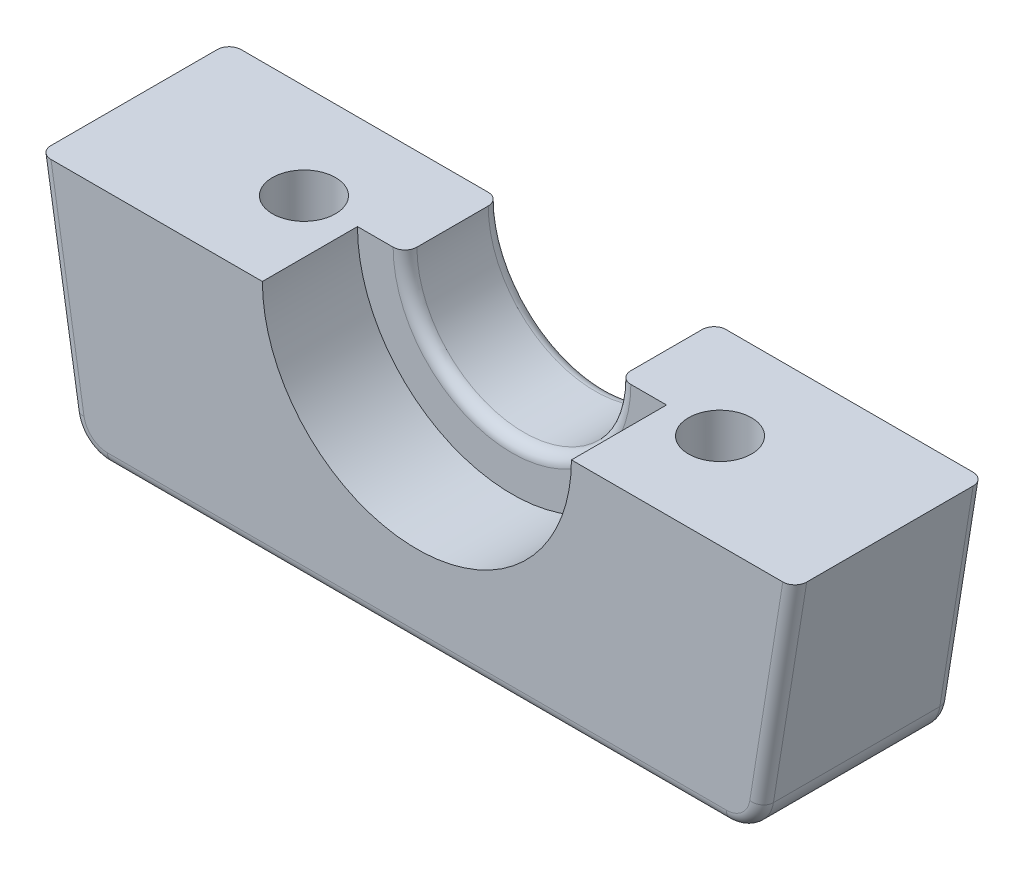
SolidWorks part; units mm, degrees
ref_plane "Płaszczyzna przednia" through (0, 0, 0) normal (0, 0, 1) x (1, 0, 0)
ref_plane "Płaszczyzna górna" through (0, 0, 0) normal (0, 1, 0) x (1, 0, 0)
ref_plane "Płaszczyzna prawa" through (0, 0, 0) normal (1, 0, 0) x (0, 0, -1)
sketch "Szkic1" plane through (0, 0, 0) normal (0, 0, 1) x (1, 0, 0)
  line L0 (0, 0) -> (28.5897, 0)
  line L1 (28.5897, 0) -> (31.7949, 20)
  line L2 (31.7949, 20) -> (0, 20)
  line L3 (0, 20) -> (0, 0)
  line L4 (35, 40) -> (60, 196) construction
  line L5 (35, 40) -> (60, 196) construction
  dimension "D2" = 20
extrude "Dodanie-wyciągnięcie1" add sketch "Szkic1" along normal mid plane 16
mirror "Lustro1" about plane through (0, 20, 8) normal (1, 0, 0) of "Dodanie-wyciągnięcie1"
sketch "Szkic2" plane through (0, 0, 8) normal (0, 0, 1) x (1, 0, 0)
  line L0 (31.7949, 20) -> (-31.7949, 20) construction
  line L1 (-13, 20) -> (13, 20)
  arc A0 (-13, 20) -> (13, 20) centre (0, 20) ccw
  dimension "D1" = 26
extrude "Wytnij-wyciągnięcie1" cut sketch "Szkic2" against normal blind 8
sketch "Szkic3" plane through (0, 0, 0) normal (0, 0, 1) x (1, 0, 0)
  line L1 (13, 20) -> (-13, 20)
  line L2 (13, 20) -> (-13, 20) construction
  arc A1 (-13, 20) -> (13, 20) centre (0, 20) ccw
  arc A2 (-13, 20) -> (13, 20) centre (0, 20) ccw construction
  arc A3 (-9, 20) -> (9, 20) centre (0, 20) ccw
  dimension "D1" = 0
  dimension "D2" = 4
extrude "Wytnij-wyciągnięcie2" cut sketch "Szkic3" against normal through all and the other way through all contours A3
sketch "Szkic4" plane through (0, 0, 0) normal (0, -1, 0) x (-1, 0, 0)
  circle A0 centre (17.5, 0) radius 2.6 construction
  circle A1 centre (-17.5, 0) radius 2.6 construction
  circle A2 centre (17.5, 0) radius 2.6
  circle A3 centre (-17.5, 0) radius 2.6
hole_wizard "Pogłębienie walcowe pod M5 Śrubę z łbem walcowym z gniazdem1" positions "Szkic5" profile "Szkic6" counterbore size "M5" standard "Ansi Metric" end condition up to next
sketch "Szkic5" plane through (0, 0, 0) normal (0, -1, 0) x (-1, 0, 0)
  point P0 (-17.5, 0)
  point P3 (17.5, 0)
sketch "Szkic6" plane through (17.5, 0, 0) normal (1, 0, 0) x (0, 0, -1)
  line L0 (0, 0) -> (0, 20)
  line L1 (0, 20) -> (2.65, 20)
  line L3 (2.65, 20) -> (2.65, 5)
  line L4 (2.65, 5) -> (5, 5)
  line L5 (5, 5) -> (5, 0)
  line L7 (5, 0) -> (0, 0)
  line L11 (0, -6.35) -> (0, 107.95) construction
  dimension "Średnica otworu na wylot" = 5.3
  dimension "Głębokość otworu na wylot" = 20
  dimension "Średnica pogłębienia walcowego" = 10
  dimension "Głębokość pogłębienia walcowego" = 5
fillet "Zaokrąglenie1" radius 3 2 edges at (-28.5897, 0, 0) (28.5897, 0, 0)
fillet "Zaokrąglenie2" radius 1 12 edges at (-30.3947, 11.2626, -8) (-30.3947, 11.2626, 8) (-27.9785, 0.717, 8) (0, 0, 8) (27.9785, 0.717, 8) (-27.9785, 0.717, -8) (0, 0, -8) (27.9785, 0.717, -8) (0, 11, -8) (30.3947, 11.2626, 8) (0, 11, 0) (30.3947, 11.2626, -8)
